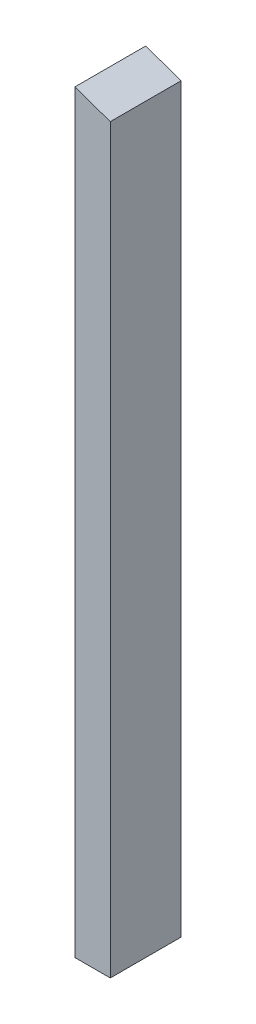
SolidWorks part; units mm, degrees
ref_plane "Спереди" through (0, 0, 0) normal (0, 0, 1) x (1, 0, 0)
ref_plane "Сверху" through (0, 0, 0) normal (0, 1, 0) x (1, 0, 0)
ref_plane "Справа" through (0, 0, 0) normal (1, 0, 0) x (0, 0, -1)
other "Configuration Table"
sketch "Эскиз1" plane through (0, 0, 0) normal (0, 1, 0) x (1, 0, 0)
  line L1 (12.5, 25) -> (-12.5, 25)
  line L2 (12.5, 25) -> (12.5, -25)
  line L3 (12.5, -25) -> (-12.5, -25)
  line L4 (-12.5, 25) -> (-12.5, -25)
  line L5 (12.5, 25) -> (-12.5, -25) construction
  line L6 (12.5, -25) -> (-12.5, 25) construction
  point P0 (0, 0)
extrude "Бобышка-Вытянуть1" add sketch "Эскиз1" along normal blind 550
sketch "Эскиз2" plane through (0, 550, 0) normal (0, 1, 0) x (1, 0, 0)
  circle A0 centre (0, 0) radius 4
extrude "Вырез-Вытянуть1" cut sketch "Эскиз2" against normal blind 10
sketch "Эскиз3" plane through (0, 0, 0) normal (0, -1, 0) x (1, 0, 0)
  circle A0 centre (0, 0) radius 4
extrude "Вырез-Вытянуть2" cut sketch "Эскиз3" against normal blind 10
sketch "Эскиз4" plane through (0, 0, 25) normal (0, 0, 1) x (1, 0, 0)
  line L2 (12.5, 550) -> (12.5, 523.5195)
  line L3 (12.5, 550) -> (12.5, 0) construction
  line L4 (0, 550) -> (0, 527.8846) construction
  line L5 (-12.5, 550) -> (12.5, 550) construction
  line L8 (-12.5, 550) -> (12.5, 550)
  line L9 (12.5, 523.5195) -> (-12.5, 532.2497)
  line L10 (-12.5, 550) -> (-12.5, 532.2497)
extrude "Вырез-Вытянуть4" cut sketch "Эскиз4" against normal blind 550
